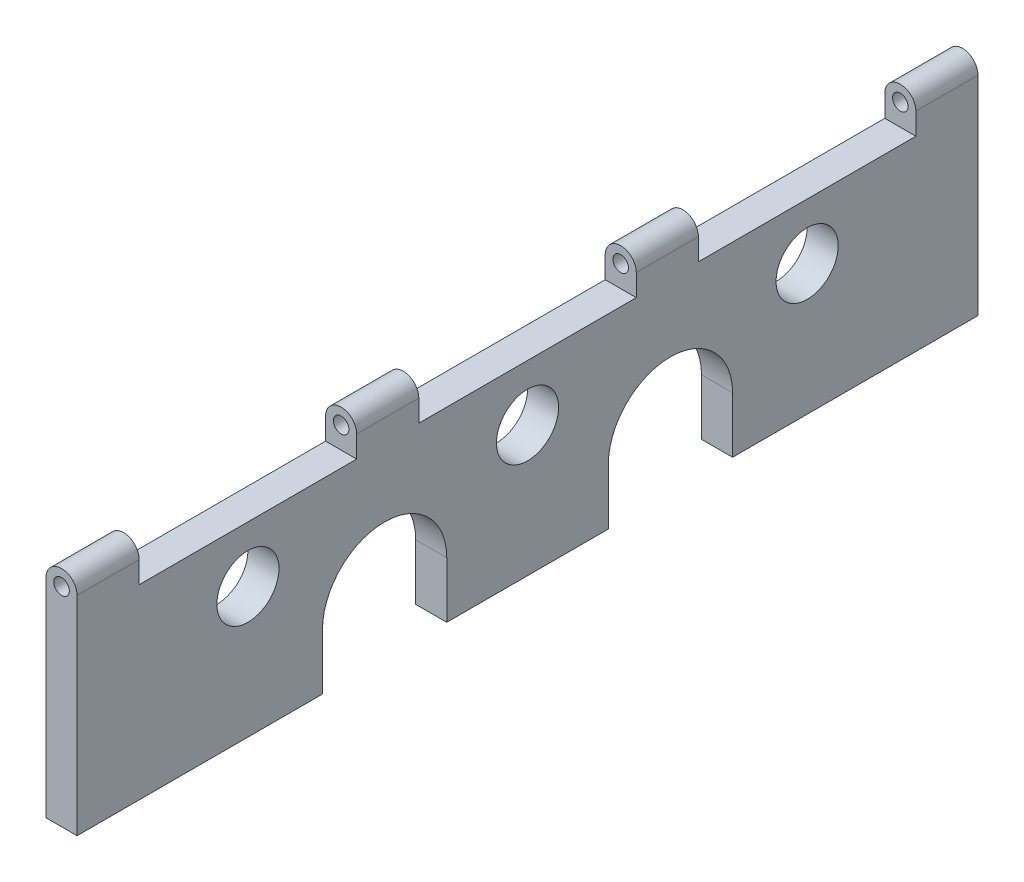
SolidWorks part; units mm, degrees
ref_plane "Спереди" through (0, 0, 0) normal (0, 0, 1) x (1, 0, 0)
ref_plane "Сверху" through (0, 0, 0) normal (0, 1, 0) x (1, 0, 0)
ref_plane "Справа" through (0, 0, 0) normal (1, 0, 0) x (0, 0, -1)
sketch "Эскиз1" plane through (0, 0, 0) normal (1, 0, 0) x (0, 0, -1)
  line L0 (27.5, 21) -> (117.5, 21) construction
  line L1 (0, 0) -> (39.5, 0)
  line L2 (0, 0) -> (0, 30)
  line L3 (0, 30) -> (145, 30)
  line L4 (145, 0) -> (145, 30)
  line L5 (72.5, 30) -> (72.5, 21) construction
  line L6 (72.5, 21) -> (72.5, 0) construction
  line L7 (49.5, 9) -> (72.5, 9) construction
  line L8 (72.5, 9) -> (95.5, 9) construction
  line L9 (39.5, 9) -> (39.5, 0)
  line L10 (59.5, 9) -> (59.5, 0)
  line L11 (105.5, 9) -> (105.5, 0)
  line L12 (85.5, 9) -> (85.5, 0)
  line L13 (59.5, 0) -> (85.5, 0)
  line L14 (105.5, 0) -> (145, 0)
  circle A0 centre (27.5, 21) radius 5
  circle A1 centre (72.5, 21) radius 5
  circle A2 centre (117.5, 21) radius 5
  arc A3 (59.5, 9) -> (39.5, 9) centre (49.5, 9) ccw
  arc A4 (105.5, 9) -> (85.5, 9) centre (95.5, 9) ccw
  dimension "D3" = 10
  dimension "D4" = 20
  dimension "D1" = 21
  dimension "D2" = 30
  dimension "D5" = 9
  dimension "D6" = 145
  dimension "D7" = 45
  dimension "D8" = 23
  dimension "D9" = 27.5
extrude "Бобышка-Вытянуть1" add sketch "Эскиз1" along normal blind 5
sketch "Эскиз2" plane through (5, 0, 0) normal (1, 0, 0) x (0, 0, -1)
  line L0 (10, 36) -> (10, 30)
  line L1 (0, 30) -> (145, 30)
  line L2 (0, 30) -> (0, 36)
  line L3 (0, 36) -> (10, 36)
  line L4 (145, 30) -> (145, 36)
  line L5 (45, 36) -> (45, 30)
  line L6 (55, 36) -> (55, 30)
  line L7 (90, 36) -> (90, 30)
  line L8 (100, 36) -> (100, 30)
  line L9 (135, 36) -> (135, 30)
  line L10 (45, 36) -> (55, 36)
  line L11 (90, 36) -> (100, 36)
  line L12 (135, 36) -> (145, 36)
  line L13 (10, 36) -> (45, 36) construction
  line L14 (55, 36) -> (90, 36) construction
  line L15 (100, 36) -> (135, 36) construction
  line L16 (145, 0) -> (145, 30) construction
  line M22 (145, 30) -> (0, 30)
  dimension "D1" = 35
  dimension "D2" = 6
extrude "Бобышка-Вытянуть2" add sketch "Эскиз2" against normal blind 5 contours L3 L2 L0 M22 | L10 L5 L1 L6 | L11 L7 L1 L8 | L12 L9 L4 M22
sketch "Эскиз3" plane through (0, 0, 0) normal (0, 0, 1) x (1, 0, 0)
  line L0 (0, 36) -> (0, 0) construction
  line L1 (5, 36) -> (5, 0) construction
  line L2 (0, 36) -> (5, 36) construction
  line L3 (0, 33.5) -> (0, 36)
  line L4 (0, 36) -> (5, 36)
  line L5 (5, 36) -> (5, 33.5)
  circle A0 centre (2.5, 33.5) radius 2.5
  circle A1 centre (2.5, 33.5) radius 1.25
  line M2 (0, 36) -> (0, 0)
  line M4 (5, 0) -> (5, 36)
  line M5 (5, 36) -> (0, 36)
  dimension "D1" = 2.5
extrude "Вырез-Вытянуть2" cut sketch "Эскиз3" against normal through all contours A0 L4 M2 | A0 M4 M5 | A1
